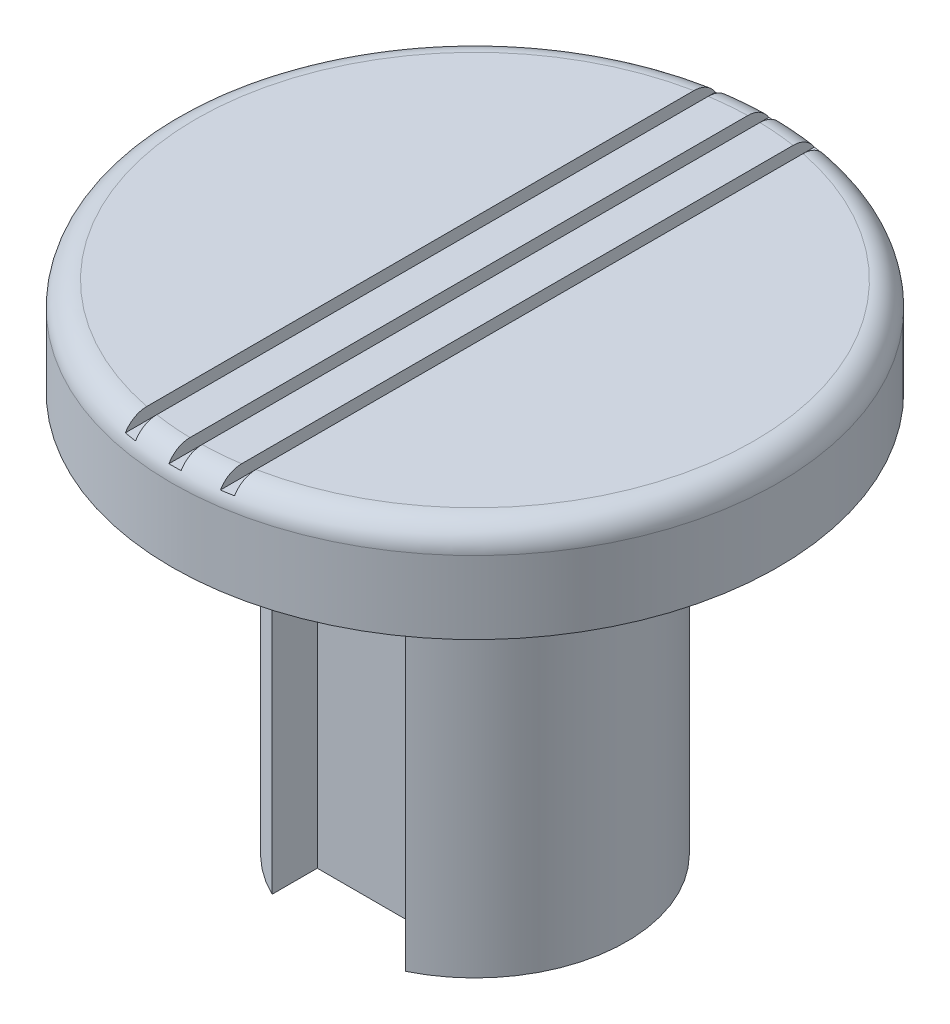
SolidWorks part; units mm, degrees
ref_plane "Front Plane" through (0, 0, 0) normal (0, 0, 1) x (1, 0, 0)
ref_plane "Top Plane" through (0, 0, 0) normal (0, 1, 0) x (1, 0, 0)
ref_plane "Right Plane" through (0, 0, 0) normal (1, 0, 0) x (0, 0, -1)
sketch "Sketch1" plane through (0, 0, 0) normal (0, 1, 0) x (1, 0, 0)
  circle A0 centre (0, 0) radius 6.25
  dimension "D1" = 12.5
extrude "Boss-Extrude1" add sketch "Sketch1" along normal blind 16.5
sketch "Sketch2" plane through (0, 16.5, 0) normal (0, 1, 0) x (1, 0, 0)
  line L0 (0, 0) -> (0, -6.25) construction
  line L2 (-2.75, -9.25) -> (2.75, -9.25)
  line L3 (-2.75, -9.25) -> (-2.75, -3.75)
  line L4 (-2.75, -3.75) -> (2.75, -3.75)
  line L5 (2.75, -9.25) -> (2.75, -3.75)
  line L6 (-2.75, -9.25) -> (2.75, -3.75) construction
  line L7 (-2.75, -3.75) -> (2.75, -9.25) construction
  circle A0 centre (0, 0) radius 6.25 construction
  point P6 (0, -6.5)
  point P11 (2.75, -7.6772)
  dimension "D1" = 3.75
  dimension "D2" = 5.5
  dimension "D3" = 5.5
extrude "Cut-Extrude1" cut sketch "Sketch2" against normal up to next
sketch "Sketch3" plane through (0, 16.5, 0) normal (0, 1, 0) x (1, 0, 0)
  circle A0 centre (0, 0) radius 12.5
  dimension "D1" = 25
extrude "Boss-Extrude2" add sketch "Sketch3" along normal blind 4
fillet "Fillet1" radius 1 1 edges at (0, 20.5, 12.5)
sketch "Sketch4" plane through (0, 20.5, 0) normal (0, 1, 0) x (1, 0, 0)
  line L0 (0, 0) -> (50000, 0) construction
  line L1 (-0.25, -15) -> (0.25, -15)
  line L2 (-0.25, -15) -> (-0.25, 15)
  line L3 (-0.25, 15) -> (0.25, 15)
  line L4 (0.25, -15) -> (0.25, 15)
  line L5 (-0.25, -15) -> (0.25, 15) construction
  line L6 (-0.25, 15) -> (0.25, -15) construction
  line L7 (0.5621, 15) -> (50000.5621, 15) construction
  line L8 (0.5621, -15) -> (50000.5621, -15) construction
  line L10 (1.75, -15) -> (2.25, -15)
  line L11 (1.75, -15) -> (1.75, 15)
  line L12 (1.75, 15) -> (2.25, 15)
  line L13 (2.25, -15) -> (2.25, 15)
  line L14 (1.75, -15) -> (2.25, 15) construction
  line L15 (1.75, 15) -> (2.25, -15) construction
  line L16 (-2.25, -15) -> (-1.75, -15)
  line L17 (-2.25, -15) -> (-2.25, 15)
  line L18 (-2.25, 15) -> (-1.75, 15)
  line L19 (-1.75, -15) -> (-1.75, 15)
  line L20 (-2.25, -15) -> (-1.75, 15) construction
  line L21 (-2.25, 15) -> (-1.75, -15) construction
  point P0 (0, 0)
  point P8 (-2, 0)
  point P13 (2, 0)
  dimension "D1" = 15
  dimension "D2" = 0.5
  dimension "D3" = 0.5
  dimension "D4" = 0.5
  dimension "D5" = 1.5
  dimension "D6" = 1.5
extrude "Cut-Extrude2" cut sketch "Sketch4" against normal blind 0.5
